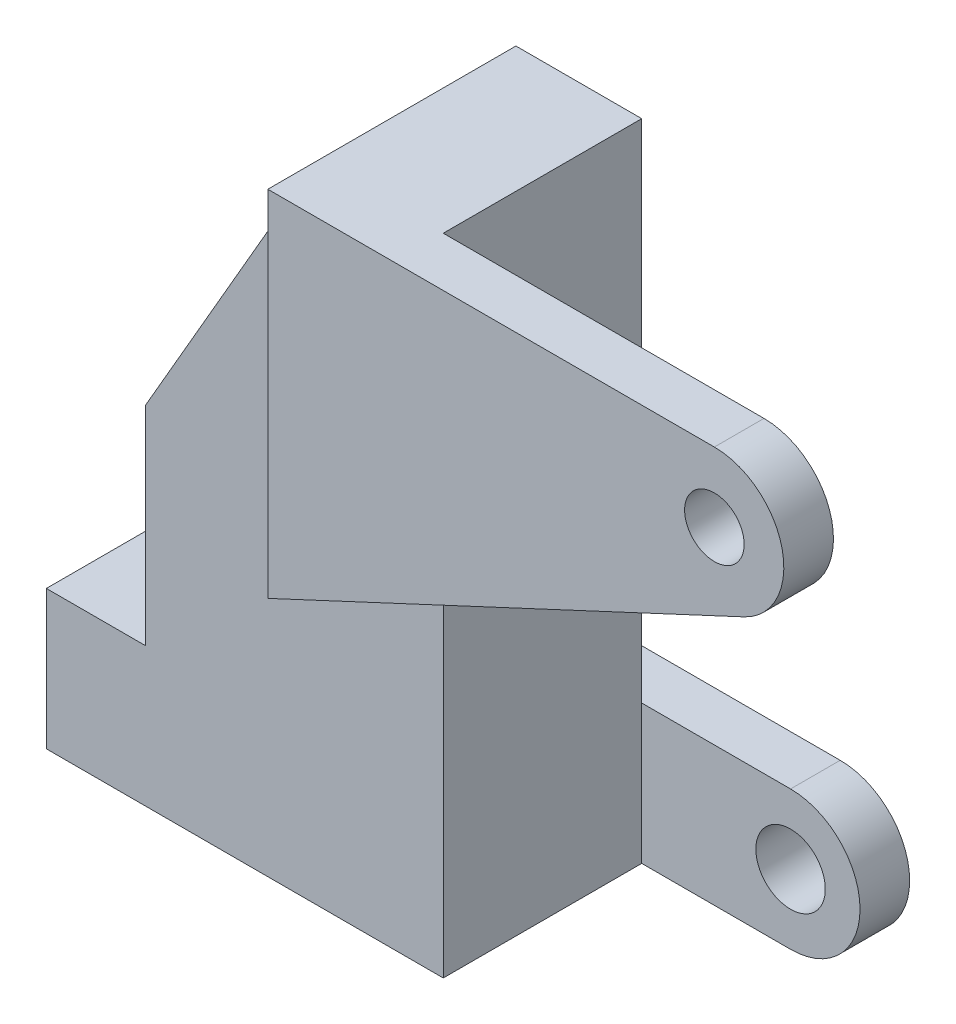
SolidWorks part; units mm, degrees
ref_plane "Front Plane" through (0, 0, 0) normal (0, 0, 1) x (1, 0, 0)
ref_plane "Top Plane" through (0, 0, 0) normal (0, 1, 0) x (1, 0, 0)
ref_plane "Right Plane" through (0, 0, 0) normal (1, 0, 0) x (0, 0, -1)
sketch "Sketch1" plane through (0, 0, 0) normal (0, 0, 1) x (1, 0, 0)
  line L0 (0, 0) -> (40, 0)
  line L1 (55, 0) -> (-55, 0) construction
  line L2 (40, 0) -> (40, 65)
  line L3 (40, 65) -> (27.3205, 65)
  line L4 (27.3205, 65) -> (10, 35)
  line L5 (10, 35) -> (10, 14)
  line L6 (10, 14) -> (0, 14)
  line L7 (0, -55) -> (0, 55) construction
  line L8 (0, 14) -> (0, 0)
  dimension "D1" = 40
  dimension "D2" = 35
  dimension "D3" = 10
  dimension "D4" = 14
  dimension "D5" = 30
  dimension "D6" = 65
extrude "Boss-Extrude1" add sketch "Sketch1" along normal blind 20
sketch "Sketch2" plane through (0, 0, 20) normal (0, 0, 1) x (1, 0, 0)
  line L0 (27.3205, 65) -> (27.3205, 29.2925)
  line L1 (27.3205, 29.2925) -> (75.2788, 51.6558)
  line L2 (72.3205, 65) -> (27.3205, 65)
  arc A1 (75.2788, 51.6558) -> (72.3205, 65) centre (72.3205, 58) ccw
  circle A2 centre (72.3205, 58) radius 3
  dimension "D2" = 14
  dimension "D4" = 6
  dimension "D1" = 45
  dimension "D3" = 65
extrude "Boss-Extrude2" add sketch "Sketch2" along normal blind 5
sketch "Sketch3" plane through (0, 0, 0) normal (0, 0, -1) x (-1, 0, 0)
  line L1 (-10, 14) -> (-55, 14)
  line L2 (-10, 14) -> (-10, 0)
  line L3 (-10, 0) -> (-55, 0)
  arc A0 (-55, 14) -> (-55, 0) centre (-55, 7) ccw
  circle A1 centre (-55, 7) radius 3.5
  dimension "D2" = 7
  dimension "D4" = 7
  dimension "D1" = 55
  dimension "D3" = 45
extrude "Boss-Extrude3" add sketch "Sketch3" along normal blind 5
